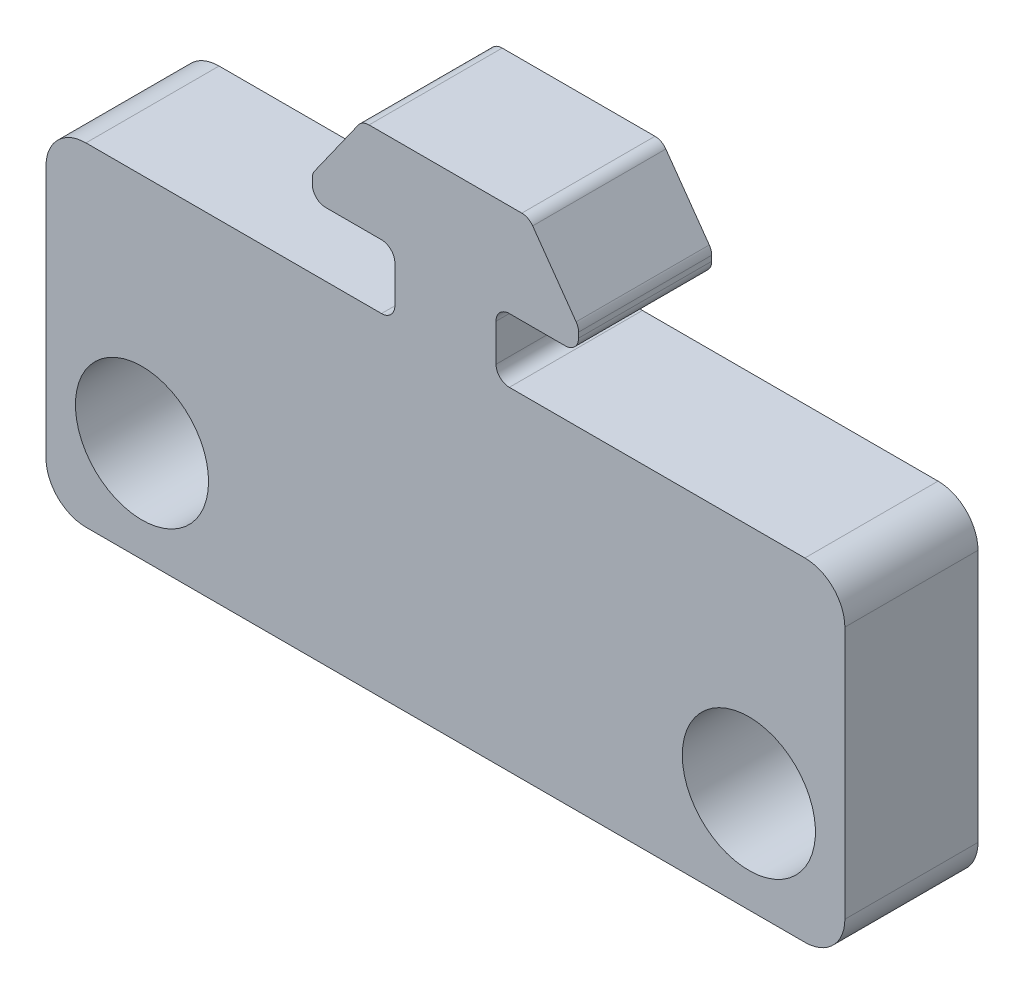
SolidWorks part; units mm, degrees
ref_plane "Front Plane" through (0, 0, 0) normal (0, 0, 1) x (1, 0, 0)
ref_plane "Top Plane" through (0, 0, 0) normal (0, 1, 0) x (1, 0, 0)
ref_plane "Right Plane" through (0, 0, 0) normal (1, 0, 0) x (0, 0, -1)
sketch "Sketch2" plane through (0, 0, 0) normal (0, 0, 1) x (1, 0, 0)
  line L0 (10, 0) -> (-10, 0)
  line L1 (-10, 0) -> (-10, 1.7099)
  line L2 (-10, 1.7099) -> (-6.2548, 7)
  line L3 (-6.2548, 7) -> (6.2548, 7)
  line L4 (0, 7) -> (0, 0)
  line L5 (0, 0) -> (0, 9.2516) construction
  line L6 (10, 1.7099) -> (6.2548, 7)
  line L7 (10, 0) -> (10, 1.7099)
  dimension "D1" = 20
  dimension "D2" = 7
extrude "Boss-Extrude1" add sketch "Sketch2" along normal blind 10 contours L4 L3 L2 L1 L0 | L0 L7 L6 L3 L4
sketch "Sketch4" plane through (0, 0, 0) normal (0, 0, 1) x (1, 0, 0)
  line L0 (-3.8, 0) -> (-3.8, -4.8)
  line L1 (10, 0) -> (-10, 0) construction
  line L2 (-3.8, -4.8) -> (-30, -4.8)
  line L3 (-30, -4.8) -> (-30, -29.8)
  line L4 (-30, -29.8) -> (30, -29.8)
  line L5 (0, 0) -> (0, -29.8) construction
  line L6 (0, -29.8) -> (0, 0)
  line L7 (3.8, 0) -> (-3.8, 0)
  line L8 (0, 0) -> (0, -30.5381) construction
  line L9 (30, -4.8) -> (30, -29.8)
  line L10 (3.8, -4.8) -> (30, -4.8)
  line L11 (3.8, 0) -> (3.8, -4.8)
  dimension "D1" = 4.8
  dimension "D2" = 3.8
  dimension "D3" = 25
  dimension "D4" = 60
extrude "Boss-Extrude2" add sketch "Sketch4" along normal blind 10 contours L6 L7 L0 L2 L3 L4 | L11 L7 L6 L4 L9 L10
sketch "Sketch5" plane through (0, 0, 0) normal (0, 0, 1) x (1, 0, 0)
  line L0 (-29.791, -22.2274) -> (26.9734, -22.2274) construction
  line L3 (0, -29.8) -> (0, 7) construction
  line L4 (-30, -29.8) -> (30, -29.8) construction
  line L5 (-6.2548, 7) -> (6.2548, 7) construction
  circle A0 centre (-22.791, -22.2274) radius 5
  circle A1 centre (22.791, -22.2274) radius 5
  point P2 (-26.9184, -21.3295)
  point P3 (-22.791, -22.2274)
  point P14 (-19.8643, -12.3)
  dimension "D1" = 7
extrude "Cut-Extrude1" cut sketch "Sketch5" along normal through all
fillet "Fillet1" radius 1 6 edges at (-10, 0, 5) (-10, 1.7099, 5) (-6.2548, 7, 5) (6.2548, 7, 5) (10, 0, 5) (10, 1.7099, 5)
fillet "Fillet2" radius 1 4 edges at (3.8, -4.8, 5) (3.8, 0, 5) (-3.8, -4.8, 5) (-3.8, 0, 5)
fillet "Fillet3" radius 3 4 edges at (-30, -4.8, 5) (-30, -29.8, 5) (30, -4.8, 5) (30, -29.8, 5)
